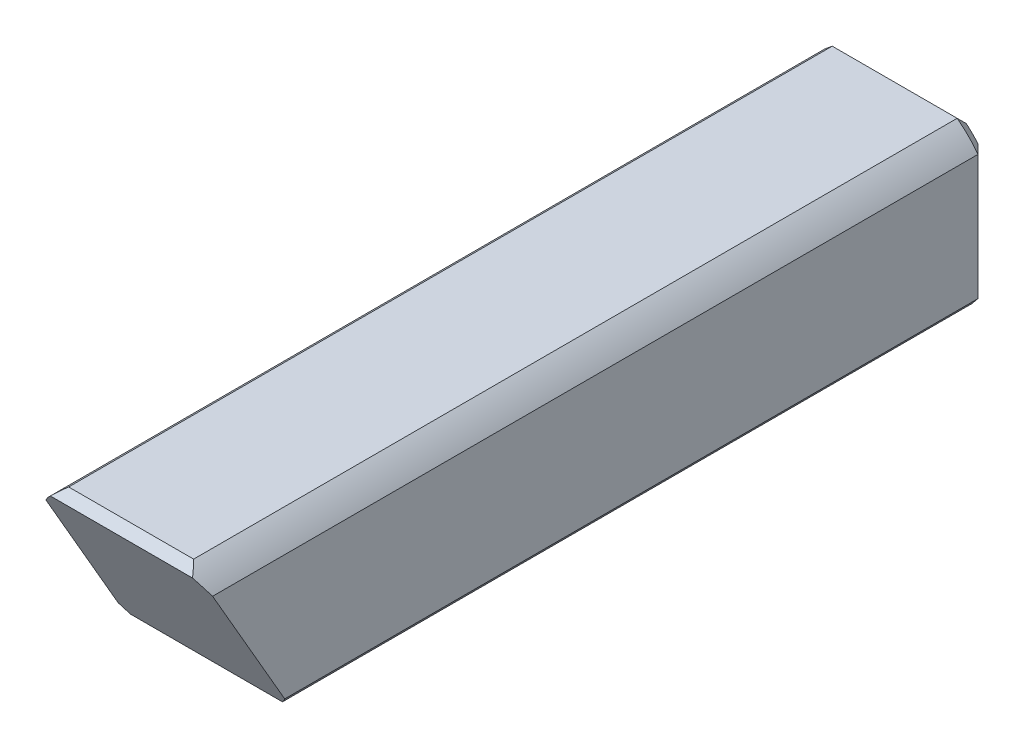
SolidWorks part; units mm, degrees
material "45"
ref_plane "前视基准面" through (0, 0, 0) normal (0, 0, 1) x (1, 0, 0)
ref_plane "上视基准面" through (0, 0, 0) normal (0, 1, 0) x (1, 0, 0)
ref_plane "右视基准面" through (0, 0, 0) normal (1, 0, 0) x (0, 0, -1)
sketch "草图1" plane through (0, 0, 0) normal (0, 0, 1) x (1, 0, 0)
  line L1 (-30, 30) -> (30, 30)
  line L2 (-30, 30) -> (-30, -30)
  line L3 (-30, -30) -> (30, -30)
  line L4 (30, 30) -> (30, -30)
  line L5 (-30, 30) -> (30, -30) construction
  line L6 (-30, -30) -> (30, 30) construction
  point P0 (0, 0)
  dimension "D1" = 60
  dimension "D2" = 60
extrude "凸台-拉伸1" add sketch "草图1" along normal blind 285 contours L1 L4 L3 L2
sketch "草图2" plane through (30, 0, 0) normal (1, 0, 0) x (0, 0, -1)
  line L0 (-285, 30) -> (-250.359, -30)
  line L1 (-285, -30) -> (0, -30) construction
  line L4 (-285, -30) -> (-250.359, -30)
  line L5 (-285, 30) -> (-285, -30) construction
  line L6 (-285, 30) -> (-285, -30)
  dimension "D1" = 120
extrude "切除-拉伸1" cut sketch "草图2" against normal blind 95 contours L4 L0 L6
sketch "草图3" plane through (0, 0, 0) normal (0, 0, -1) x (1, 0, 0)
  circle A4 centre (0, 0) radius 37.5
  dimension "D1" = 75
extrude "切除-拉伸2" cut sketch "草图3" against normal through all flip side to cut
chamfer "倒角1" distance 3 distance2 5 2 edges at (0, -30, 250.359) (0, 30, 285)
chamfer "倒角2" distance 5 angle 45 8 edges at (30, 0, 0) (26.5165, 26.5165, 0) (0, 30, 0) (-26.5165, 26.5165, 0) (-30, 0, 0) (-26.5165, -26.5165, 0) (0, -30, 0) (26.5165, -26.5165, 0)
